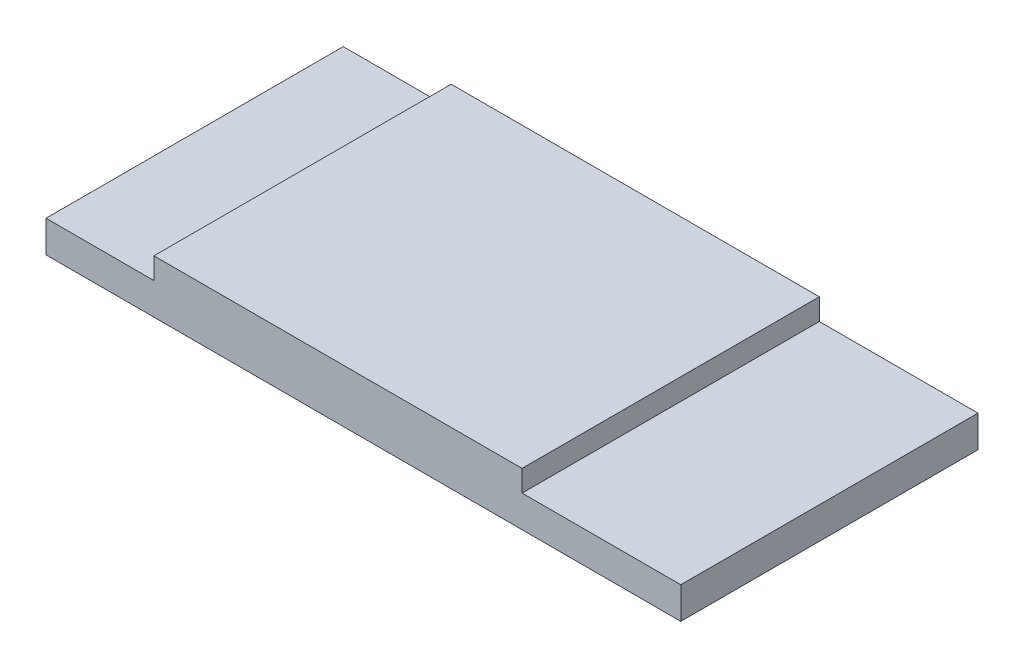
SolidWorks part; units mm, degrees
ref_plane "Front Plane" through (0, 0, 0) normal (0, 0, 1) x (1, 0, 0)
ref_plane "Top Plane" through (0, 0, 0) normal (0, 1, 0) x (1, 0, 0)
ref_plane "Right Plane" through (0, 0, 0) normal (1, 0, 0) x (0, 0, -1)
sketch "Sketch1" plane through (0, 0, 0) normal (0, 1, 0) x (1, 0, 0)
  line L1 (0, 0) -> (40, 0)
  line L2 (0, 0) -> (0, 18.73)
  line L3 (0, 18.73) -> (40, 18.73)
  line L4 (40, 0) -> (40, 18.73)
  dimension "D1" = 40
  dimension "D2" = 18.73
extrude "Boss-Extrude1" add sketch "Sketch1" along normal blind 2
sketch "Sketch2" plane through (0, 2, 0) normal (0, 1, 0) x (1, 0, 0)
  line L0 (40, 18.73) -> (0, 18.73) construction
  line L1 (6.8, 18.73) -> (30, 18.73)
  line L2 (6.8, 18.73) -> (6.8, 0)
  line L3 (6.8, 0) -> (30, 0)
  line L4 (30, 18.73) -> (30, 0)
  line L5 (0, 18.73) -> (0, 0) construction
  dimension "D1" = 6.8
  dimension "D2" = 23.2
  dimension "D3" = 18.73
extrude "Boss-Extrude2" add sketch "Sketch2" along normal blind 1.35
